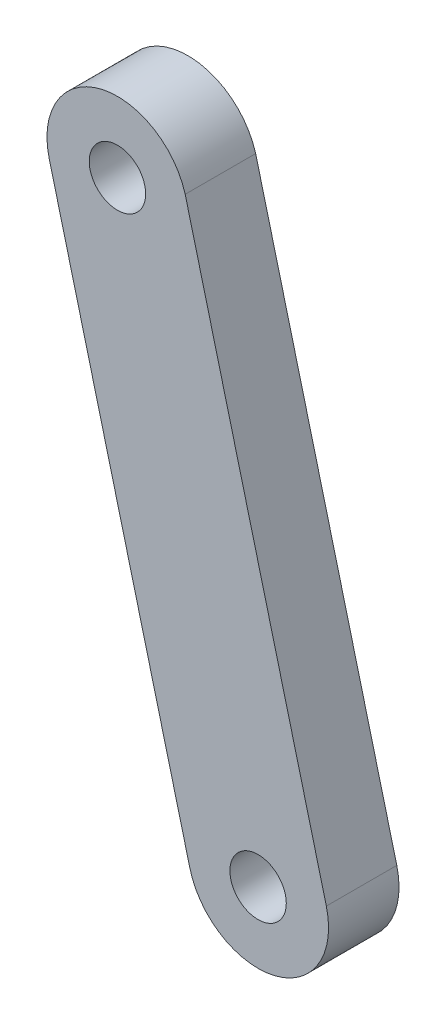
SolidWorks part; units mm, degrees
ref_plane "Front Plane" through (0, 0, 0) normal (0, 0, 1) x (1, 0, 0)
ref_plane "Top Plane" through (0, 0, 0) normal (0, 1, 0) x (1, 0, 0)
ref_plane "Right Plane" through (0, 0, 0) normal (1, 0, 0) x (0, 0, -1)
sketch "Sketch1" plane through (0, 0, 0) normal (0, 0, 1) x (1, 0, 0)
  line L0 (-32.1524, -85.2888) -> (-23.8725, -117.3113) construction
  line L1 (-34.573, -85.9147) -> (-29.5664, -105.2779)
  line L2 (-29.7497, -84.5971) -> (-24.7431, -103.9604)
  arc A0 (-29.7497, -84.5971) -> (-34.573, -85.9147) centre (-32.1524, -85.2888) ccw
  circle A1 centre (-32.1524, -85.2888) radius 1
  arc A2 (-34.573, -85.9147) -> (-29.7497, -84.5971) centre (-32.1524, -85.2888) ccw construction
  arc A3 (-29.5834, -105.2119) -> (-24.7431, -103.9604) centre (-27.1633, -104.5861) ccw
  circle A4 centre (-27.1633, -104.5861) radius 1
  dimension "D1" = 2
  dimension "D2" = 2
  dimension "D3" = 20
extrude "Boss-Extrude1" add sketch "Sketch1" along normal blind 2.5
